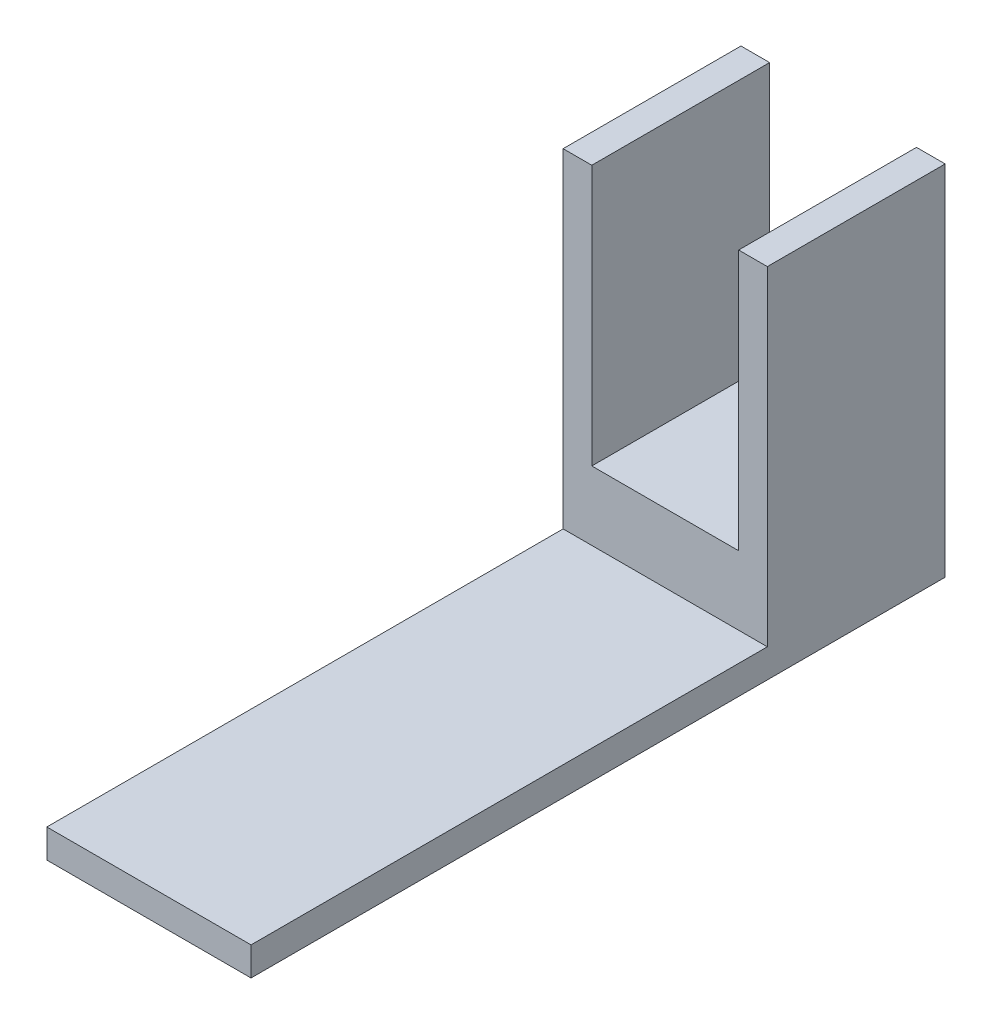
SolidWorks part; units mm, degrees
ref_plane "Front Plane" through (0, 0, 0) normal (0, 0, 1) x (1, 0, 0)
ref_plane "Top Plane" through (0, 0, 0) normal (0, 1, 0) x (1, 0, 0)
ref_plane "Right Plane" through (0, 0, 0) normal (1, 0, 0) x (0, 0, -1)
sketch "Sketch1" plane through (0, 0, 0) normal (0, 1, 0) x (1, 0, 0)
  line L1 (0, 0) -> (12.8, 0)
  line L2 (0, 0) -> (0, 15.5)
  line L3 (0, 15.5) -> (12.8, 15.5)
  line L4 (12.8, 0) -> (12.8, 15.5)
  dimension "D1" = 15.5
  dimension "D2" = 12.8
extrude "Boss-Extrude1" add sketch "Sketch1" along normal blind 2 and the other way blind 4
sketch "Sketch2" plane through (12.8, 0, 0) normal (1, 0, 0) x (0, 0, -1)
  line L1 (0, 0) -> (15.5, 0)
  line L2 (0, 0) -> (0, 24.7)
  line L3 (0, 24.7) -> (15.5, 24.7)
  line L4 (15.5, 0) -> (15.5, 24.7)
  line L5 (0, -4) -> (15.5, -4)
  line L6 (0, -4) -> (0, 0)
  line L7 (0, 0) -> (15.5, 0)
  line L8 (15.5, -4) -> (15.5, 0)
  line M2 (0, -4) -> (15.5, -4)
  line M3 (15.5, -4) -> (15.5, 2)
  line M4 (15.5, 2) -> (0, 2)
  line M5 (0, 2) -> (0, -4)
  dimension "D1" = 24.7
extrude "Boss-Extrude2" add sketch "Sketch2" along normal blind 2.5 contours L1 M5 M2 M3 | L4 L3 L2 M4 | L1 M5 M3 M4
sketch "Sketch3" plane through (0, 0, 0) normal (-1, 0, 0) x (0, 0, 1)
  line L2 (0, 0) -> (0, 24.7)
  line L3 (0, 24.7) -> (-15.5, 24.7)
  line L4 (-15.5, 0) -> (-15.5, 24.7)
  line L6 (-15.5, 0) -> (-15.5, -4)
  line L7 (-15.5, -4) -> (0, -4)
  line L8 (0, 0) -> (0, -4)
  dimension "D1" = 24.7
extrude "Boss-Extrude3" add sketch "Sketch3" along normal blind 2.5
sketch "Sketch5" plane through (0, -4, 0) normal (0, -1, 0) x (1, 0, 0)
  line L0 (-2.5, -15.5) -> (-2.5, 0) construction
  line L1 (15.3, 45) -> (-2.5, 45)
  line L2 (15.3, 45) -> (15.3, -15.5)
  line L3 (15.3, -15.5) -> (-2.5, -15.5)
  line L4 (-2.5, 45) -> (-2.5, -15.5)
  line L9 (15.3, 0) -> (15.3, -15.5) construction
  line L10 (15.3, -15.5) -> (-2.5, -15.5) construction
  line L11 (-2.5, 0) -> (15.3, 0) construction
  dimension "D2" = 0
  dimension "D1" = 0
  dimension "D4" = 0
  dimension "D3" = 45
extrude "Boss-Extrude5" add sketch "Sketch5" along normal blind 2.5
equation "\"D1@Sketch5\"=\"D2@Sketch5\""
equation "\"D4@Sketch5\"=\"D2@Sketch5\""
